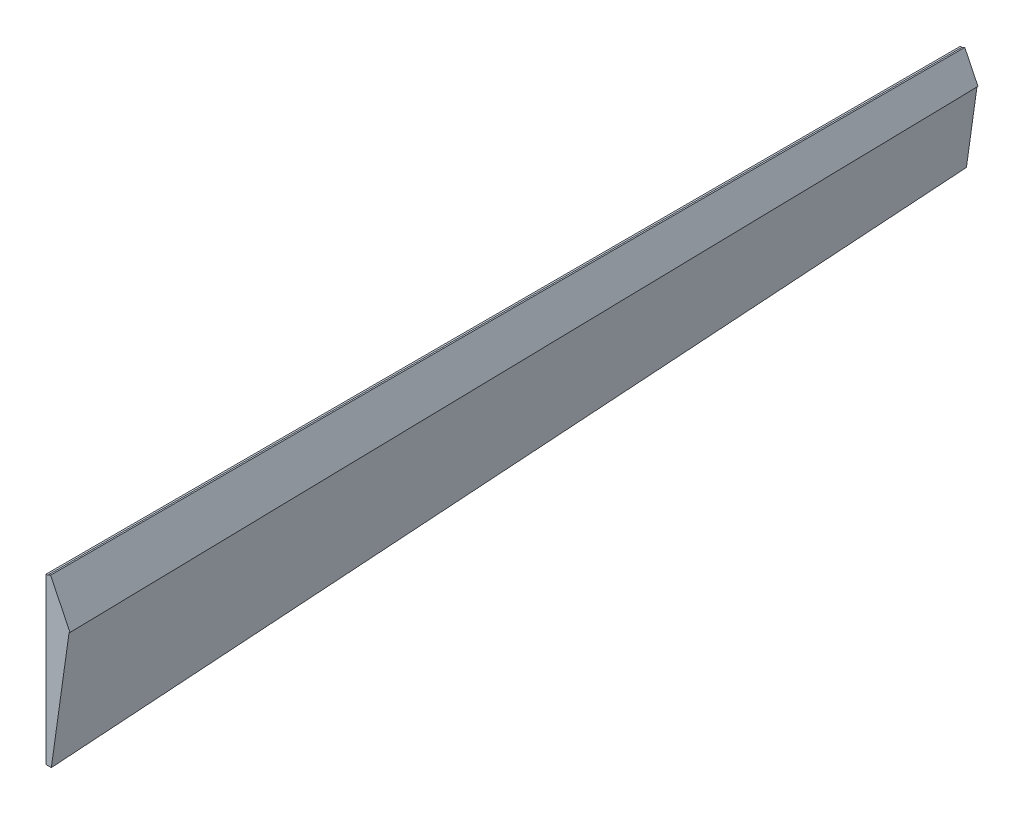
SolidWorks part; units mm, degrees
ref_plane "前视基准面" through (0, 0, 0) normal (0, 0, 1) x (1, 0, 0)
ref_plane "上视基准面" through (0, 0, 0) normal (0, 1, 0) x (1, 0, 0)
ref_plane "右视基准面" through (0, 0, 0) normal (1, 0, 0) x (0, 0, -1)
sketch "草图2" plane through (0, 0, 0) normal (0, 0, 1) x (1, 0, 0)
  line L0 (0, -64.0468) -> (3.9092, -64.0468)
  line L1 (3.9092, -64.0468) -> (10.5895, -16.5138)
  line L2 (0, 0) -> (0, -64.0468)
  line L3 (10.5895, -16.5138) -> (11.1991, -16.2165)
  line L4 (1.0646, 0) -> (2.8622, 0.8767)
  line L5 (2.8622, 0.8767) -> (11.1991, -16.2165)
  line L6 (1.0646, 0) -> (0, 0)
ref_plane "基准面5" through (0, 0, 575.24) normal (0, 0, 1) x (1, 0, 0)
sketch "草图4" plane through (0, 0, 575.24) normal (0, 0, 1) x (1, 0, 0)
  line L0 (0, -103.7626) -> (3.3579, -103.7626)
  line L1 (0, -103.7626) -> (0, 0)
  line L2 (14.5199, -24.5082) -> (3.3579, -103.7626)
  line L3 (1.0646, 0) -> (2.8622, 0.8767)
  line L4 (2.8622, 0.8767) -> (15.1042, -24.2232)
  line L5 (15.1042, -24.2232) -> (14.5199, -24.5082)
  line L6 (1.0646, 0) -> (0, 0)
loft "放样1" add profiles "草图2", "草图4"
